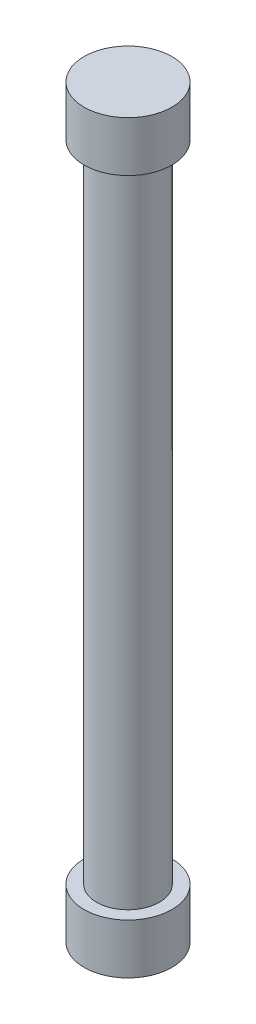
SolidWorks part; units mm, degrees
ref_plane "Front Plane" through (0, 0, 0) normal (0, 0, 1) x (1, 0, 0)
ref_plane "Top Plane" through (0, 0, 0) normal (0, 1, 0) x (1, 0, 0)
ref_plane "Right Plane" through (0, 0, 0) normal (1, 0, 0) x (0, 0, -1)
sketch "Sketch1" plane through (0, 0, 0) normal (0, 1, 0) x (1, 0, 0)
  circle A0 centre (0, 0) radius 2.5
  dimension "D1" = 5
extrude "Boss-Extrude1" add sketch "Sketch1" along normal blind 51.4
sketch "Sketch2" plane through (0, 51.4, 0) normal (0, 1, 0) x (1, 0, 0)
  circle A0 centre (0, 0) radius 3.5
  dimension "D1" = 7
extrude "Boss-Extrude2" add sketch "Sketch2" along normal blind 4
sketch "Sketch3" plane through (0, 0, 0) normal (0, -1, 0) x (1, 0, 0)
  circle A0 centre (0, 0) radius 3.5
  dimension "D1" = 7
extrude "Boss-Extrude3" add sketch "Sketch3" along normal blind 4
